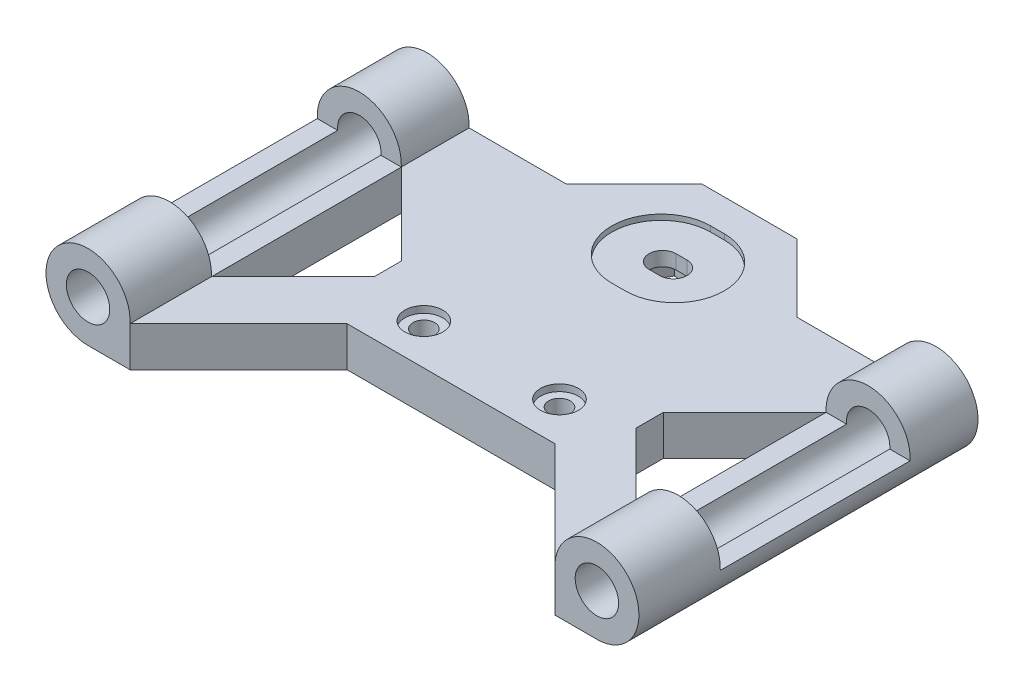
SolidWorks part; units mm, degrees
ref_plane "前视基准面" through (0, 0, 0) normal (0, 0, 1) x (1, 0, 0)
ref_plane "上视基准面" through (0, 0, 0) normal (0, 1, 0) x (1, 0, 0)
ref_plane "右视基准面" through (0, 0, 0) normal (1, 0, 0) x (0, 0, -1)
other "Configuration Table"
sketch "草图1" plane through (0, 0, 0) normal (0, 0, 1) x (1, 0, 0)
  line L0 (-46.5078, 2.4292) -> (-8.9878, 2.4292)
  line L1 (-43.4117, 5.3742) -> (-12.0839, 5.3742)
  line L3 (-37.4778, 5.3742) -> (-18.0178, 5.3742) construction
  circle A0 centre (-46.5078, 5.5292) radius 1.6
  circle A1 centre (-8.9878, 5.5292) radius 1.6
  circle A2 centre (-46.5078, 5.5292) radius 3.1
  circle A3 centre (-8.9878, 5.5292) radius 3.1
  circle A5 centre (-8.9878, 5.5292) radius 1.525 construction
  circle A6 centre (-46.5078, 5.5292) radius 1.525 construction
  dimension "D1" = 3.2
  dimension "D2" = 1.5
extrude "凸台-拉伸1" add sketch "草图1" along normal blind 25 contours A2 A0 | A3 L1 A2 L0 | A3 A1
sketch "草图2" plane through (0, 5.3742, 0) normal (0, 1, 0) x (1, 0, 0)
  line L0 (-19.2478, 0) -> (-24.2478, 5)
  line L1 (-43.4117, 0) -> (-12.0839, 0) construction
  line L2 (-24.2478, 5) -> (-31.2478, 5)
  line L4 (-31.2478, 5) -> (-36.2478, 0)
  line L6 (-27.7478, 17.7449) -> (-27.7478, -46.0927) construction
  line L9 (-43.4078, -25) -> (-43.4078, 0) construction
  line L10 (-12.0878, 0) -> (-12.0878, -25) construction
  line L11 (-36.2478, 0) -> (-19.2478, 0)
  dimension "D1" = 5
  dimension "D2" = 7
  dimension "D3" = 45
extrude "凸台-拉伸2" add sketch "草图2" against normal up to surface (2.945 mm away) up to face at (-27.7478, 2.4292, 12.5)
sketch "草图3" plane through (0, 5.3742, 0) normal (0, 1, 0) x (1, 0, 0)
  line L0 (-28.1478, -1) -> (-27.3478, -1) construction
  line L1 (-28.1478, 0) -> (-27.3478, 0)
  line L2 (-28.1478, -2) -> (-27.3478, -2)
  line L3 (-24.2478, 5) -> (-31.2478, 5) construction
  arc A0 (-28.1478, 0) -> (-28.1478, -2) centre (-28.1478, -1) ccw
  arc A1 (-27.3478, -2) -> (-27.3478, 0) centre (-27.3478, -1) ccw
  point P2 (-27.7478, -1)
  point P10 (-27.7478, 5)
  dimension "D1" = 1
  dimension "D2" = 0.8
  dimension "15" = 6
extrude "切除-拉伸1" cut sketch "草图3" against normal through all
sketch "草图5" plane through (0, 2.4292, 0) normal (0, -1, 0) x (-1, 0, 0)
  line L17 (29.7149, -1) -> (28.5313, 1.05)
  line L18 (28.5313, 1.05) -> (26.1642, 1.05)
  line L19 (26.1642, 1.05) -> (24.9806, -1)
  line L20 (24.9806, -1) -> (26.1642, -3.05)
  line L21 (26.1642, -3.05) -> (28.5313, -3.05)
  line L22 (28.5313, -3.05) -> (29.7149, -1)
  line L23 (30.5149, -1) -> (29.3313, 1.05)
  line L24 (29.3313, 1.05) -> (26.9642, 1.05)
  line L25 (26.9642, 1.05) -> (25.7806, -1)
  line L26 (25.7806, -1) -> (26.9642, -3.05)
  line L27 (26.9642, -3.05) -> (29.3313, -3.05)
  line L28 (29.3313, -3.05) -> (30.5149, -1)
  circle A4 centre (27.3478, -1) radius 2.05 construction
  arc A5 (27.3478, 0) -> (27.3478, -2) centre (27.3478, -1) ccw construction
  circle A6 centre (28.1478, -1) radius 2.05 construction
  arc A7 (28.1478, -2) -> (28.1478, 0) centre (28.1478, -1) ccw construction
  line M17 (27.3478, 0) -> (28.1478, 0)
  arc M18 (28.1478, 0) -> (28.1478, -2) centre (28.1478, -1) cw
  line M19 (28.1478, -2) -> (27.3478, -2)
  arc M20 (27.3478, -2) -> (27.3478, 0) centre (27.3478, -1) cw
  dimension "D1" = 4.1
extrude "切除-拉伸4" cut sketch "草图5" against normal blind 1.5 contours L26 L25 L18 L19 L20 L21 | L25 L26 L21 L22 L17 L18 M20 M17 M18 M19 | L27 L28 L23 L24 L17 L22
sketch "草图6" plane through (0, 5.3742, 0) normal (0, 1, 0) x (1, 0, 0)
  line L1 (-27.7478, -17.7348) -> (-27.7478, -33.5164) construction
  line L2 (-43.4117, -25) -> (-12.0839, -25) construction
  circle A0 centre (-32.7478, -14) radius 0.8
  circle A1 centre (-22.7478, -14) radius 0.8
  arc A3 (-27.3478, -2) -> (-27.3478, 0) centre (-27.3478, -1) ccw construction
  point P6 (-27.7478, -25)
  dimension "D2" = 1.6
  dimension "D3" = 13
  dimension "D1" = 10
extrude "切除-拉伸5" cut sketch "草图6" against normal through all
sketch "草图7" plane through (0, 5.3742, 0) normal (0, 1, 0) x (1, 0, 0)
  line L0 (-35.4078, -17) -> (-20.0839, -17)
  line L1 (-20.0839, -17) -> (-12.0839, -25)
  line L2 (-43.4078, -25) -> (-35.4078, -17)
  line L3 (-43.4117, -25) -> (-12.0839, -25) construction
  line L4 (-43.4078, -5) -> (-35.4078, -13)
  line L5 (-43.4078, -25) -> (-43.4078, 0) construction
  line L6 (-35.4078, -13) -> (-35.4078, -17)
  line L7 (-12.0878, -5) -> (-20.0839, -12.9961)
  line L8 (-12.0878, 0) -> (-12.0878, -25) construction
  line L9 (-20.0839, -12.9961) -> (-20.0839, -17)
  line L10 (-43.4078, -19) -> (-35.4078, -11)
  line L11 (-20.0839, -11.0039) -> (-12.0878, -19)
  line L12 (-27.7478, 9.0219) -> (-27.7478, -36.5602) construction
  line L13 (-24.2478, 5) -> (-31.2478, 5) construction
  line L14 (-43.4117, 0) -> (-36.2478, 0) construction
  line L15 (-43.4078, -5) -> (-43.4078, -19)
  line L16 (-12.0878, -5) -> (-12.0878, -19)
  line L17 (-37.4078, -11) -> (-37.4078, -13)
  line L18 (-18.0878, -11) -> (-18.0878, -13)
  circle A0 centre (-32.7478, -14) radius 0.8 construction
  point P26 (-27.7478, 5)
  dimension "D1" = 45
  dimension "D2" = 6
  dimension "D3" = 3
  dimension "D4" = 45
  dimension "D5" = 45
  dimension "D6" = 5
  dimension "D7" = 6
extrude "切除-拉伸6" cut sketch "草图7" against normal through all
sketch "草图9" plane through (-12.0878, 0, 0) normal (-1, 0, 0) x (0, 0, 1)
  line L0 (25, 3.9292) -> (25, 7.1292) construction
  line L1 (25, 3.9292) -> (25, 7.1292)
  line L2 (0, 8.6292) -> (0, 2.4292) construction
  line L3 (25, 3.9292) -> (0, 3.9292)
  line L4 (25, 3.9292) -> (25, 8.6292)
  line L5 (25, 8.6292) -> (0, 8.6292)
  line L6 (0, 3.9292) -> (0, 8.6292)
  line L7 (25, 8.6292) -> (0, 8.6292) construction
  line L8 (5, 5.3742) -> (19, 5.3742) construction
  line L9 (5, 5.3742) -> (19, 5.3742)
  line L12 (19, 5.3742) -> (5, 5.3742)
  line L13 (5, 5.3742) -> (5, 2.4292)
  line L14 (5, 2.4292) -> (19, 2.4292)
  line L15 (19, 2.4292) -> (19, 5.3742)
  line L17 (5, 8.6292) -> (5, 2.4292)
  line L18 (5, 2.4292) -> (19, 2.4292)
  line L19 (19, 2.4292) -> (19, 8.6292)
  line M5 (19, 5.3742) -> (5, 5.3742)
  dimension "D1" = 0
extrude "切除-拉伸9" cut sketch "草图9" against normal through all contours L19 L5 L17 M5
ref_plane "基准面1" through (-27.7478, 0, 0) normal (1, 0, 0) x (0, 0, -1)
mirror "镜向1" about plane through (-27.7478, 0, 0) normal (1, 0, 0) of "切除-拉伸9"
sketch "草图10" plane through (0, 5.3742, 0) normal (0, 1, 0) x (1, 0, 0)
  circle A0 centre (-22.7478, -14) radius 1.4
  circle A1 centre (-32.7478, -14) radius 1.4
  circle A2 centre (-22.7478, -14) radius 0.8 construction
  circle A3 centre (-32.7478, -14) radius 0.8 construction
  dimension "D1" = 2.8
extrude "切除-拉伸11" cut sketch "草图10" against normal blind 0.5
sketch "草图11" plane through (0, 5.3742, 0) normal (0, 1, 0) x (1, 0, 0)
  line L0 (-27.2478, -1) -> (-28.2478, -1) construction
  line L1 (-27.2478, -4.65) -> (-28.2478, -4.65)
  line L2 (-27.2478, 2.65) -> (-28.2478, 2.65)
  arc A0 (-27.2478, -4.65) -> (-27.2478, 2.65) centre (-27.2478, -1) ccw
  arc A1 (-28.2478, 2.65) -> (-28.2478, -4.65) centre (-28.2478, -1) ccw
  circle A2 centre (-27.7478, -1) radius 3.65 construction
  point P2 (-27.7478, -1)
  point P7 (0, 0)
  dimension "D1" = 1
extrude "切除-拉伸12" cut sketch "草图11" against normal blind 0.4
